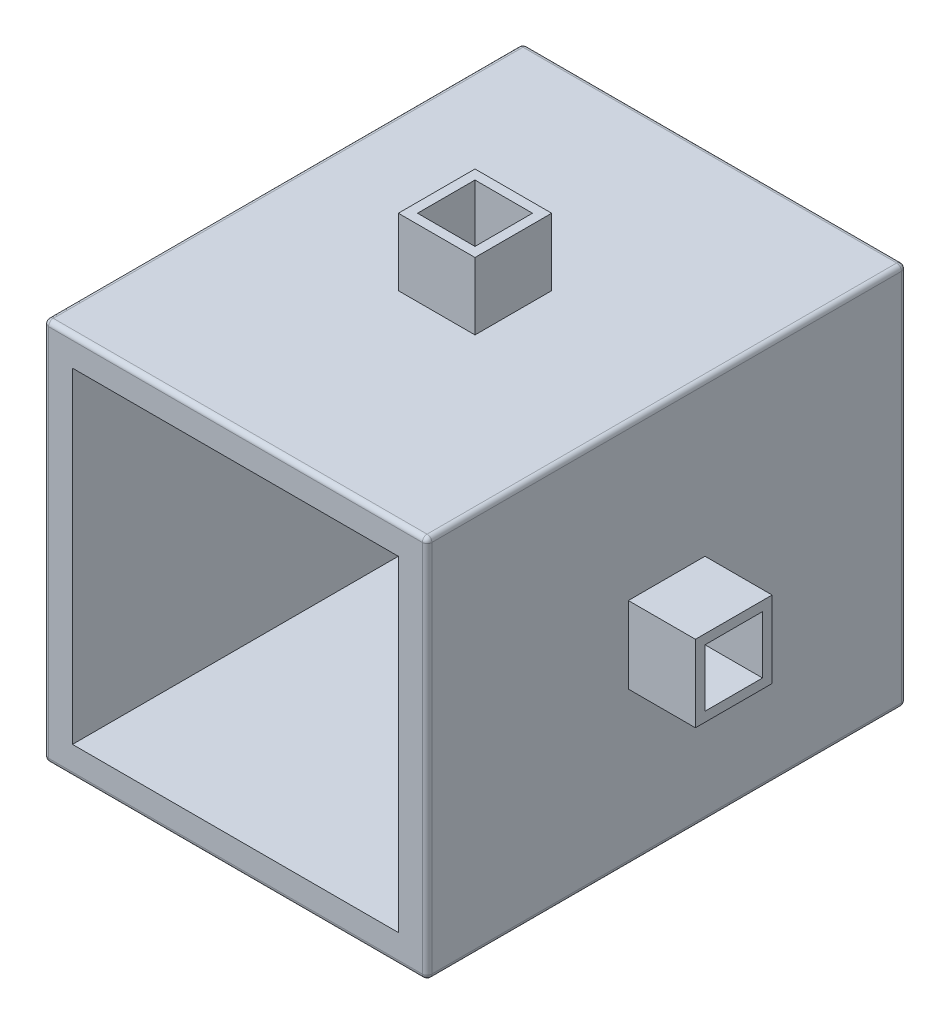
SolidWorks part; units mm, degrees
ref_plane "Front Plane" through (0, 0, 0) normal (0, 0, 1) x (1, 0, 0)
ref_plane "Top Plane" through (0, 0, 0) normal (0, 1, 0) x (1, 0, 0)
ref_plane "Right Plane" through (0, 0, 0) normal (1, 0, 0) x (0, 0, -1)
sketch "Sketch1" plane through (0, 0, 0) normal (0, 0, 1) x (1, 0, 0)
  line L1 (50.8, -50.8) -> (-50.8, -50.8)
  line L2 (50.8, -50.8) -> (50.8, 50.8)
  line L3 (50.8, 50.8) -> (-50.8, 50.8)
  line L4 (-50.8, -50.8) -> (-50.8, 50.8)
  line L5 (50.8, -50.8) -> (-50.8, 50.8) construction
  line L6 (50.8, 50.8) -> (-50.8, -50.8) construction
  point P0 (0, 0)
  dimension "D1" = 101.6
  dimension "D2" = 101.6
extrude "Boss-Extrude1" add sketch "Sketch1" along normal blind 127
sketch "Sketch2" plane through (0, 0, 127) normal (0, 0, 1) x (1, 0, 0)
  line L8 (-43.18, 43.18) -> (-43.18, -43.18)
  line L9 (-43.18, -43.18) -> (43.18, -43.18)
  line L10 (43.18, -43.18) -> (43.18, 43.18)
  line L11 (43.18, 43.18) -> (-43.18, 43.18)
  line L12 (-43.18, 43.18) -> (-43.18, -43.18)
  line L13 (-43.18, -43.18) -> (43.18, -43.18)
  line L14 (43.18, -43.18) -> (43.18, 43.18)
  line L15 (43.18, 43.18) -> (-43.18, 43.18)
  dimension "D1" = 7.62
extrude "Cut-Extrude1" cut sketch "Sketch2" against normal blind 116.84
sketch "Sketch4" plane through (0, 50.8, 0) normal (0, 1, 0) x (1, 0, 0)
  line L0 (0, 0) -> (0, -127) construction
  line L1 (10.16, -73.66) -> (-10.16, -73.66)
  line L2 (10.16, -73.66) -> (10.16, -53.34)
  line L3 (10.16, -53.34) -> (-10.16, -53.34)
  line L4 (-10.16, -73.66) -> (-10.16, -53.34)
  line L5 (10.16, -73.66) -> (-10.16, -53.34) construction
  line L6 (10.16, -53.34) -> (-10.16, -73.66) construction
  line L7 (50.8, -127) -> (-50.8, -127) construction
  line L8 (50.8, -63.5) -> (-50.8, -63.5) construction
  line L9 (50.8, -127) -> (50.8, 0) construction
  line L10 (-50.8, -127) -> (-50.8, 0) construction
  line L11 (7.62, -55.88) -> (-7.62, -55.88)
  line L12 (-7.62, -71.12) -> (-7.62, -55.88)
  line L13 (7.62, -71.12) -> (-7.62, -71.12)
  line L14 (7.62, -71.12) -> (7.62, -55.88)
  point P0 (0, -63.5)
  dimension "D1" = 20.32
  dimension "D2" = 20.32
  dimension "D3" = 2.54
extrude "Boss-Extrude2" add sketch "Sketch4" along normal blind 17.78
sketch "Sketch6" plane through (0, 50.8, 0) normal (0, 1, 0) x (1, 0, 0)
  line L0 (0, 0) -> (0, -127) construction
  line L1 (50.8, -127) -> (-50.8, -127) construction
  line L2 (50.8, -63.5) -> (-50.8, -63.5) construction
  line L3 (50.8, -127) -> (50.8, 0) construction
  line L4 (-50.8, -127) -> (-50.8, 0) construction
  circle A0 centre (0, -63.5) radius 7.62
  dimension "D1" = 15.24
extrude "Cut-Extrude2" cut sketch "Sketch6" against normal blind 1.27
mirror "Mirror1" about plane through (0, 0, 0) normal (0, 1, 0) of "Cut-Extrude2", "Boss-Extrude2"
sketch "Sketch7" plane through (50.8, 0, 0) normal (1, 0, 0) x (0, 0, -1)
  line L0 (-63.5, 50.8) -> (-63.5, -50.8) construction
  line L1 (-127, 50.8) -> (0, 50.8) construction
  line L2 (-127, -50.8) -> (0, -50.8) construction
  line L3 (0, 0) -> (-127, 0) construction
  line L4 (-127, -50.8) -> (-127, 50.8) construction
  line L6 (-53.34, -10.16) -> (-73.66, -10.16)
  line L7 (-53.34, -10.16) -> (-53.34, 10.16)
  line L8 (-53.34, 10.16) -> (-73.66, 10.16)
  line L9 (-73.66, -10.16) -> (-73.66, 10.16)
  line L10 (-53.34, -10.16) -> (-73.66, 10.16) construction
  line L11 (-53.34, 10.16) -> (-73.66, -10.16) construction
  line L12 (-55.88, -7.62) -> (-71.12, -7.62)
  line L13 (-71.12, -7.62) -> (-71.12, 7.62)
  line L14 (-55.88, 7.62) -> (-71.12, 7.62)
  line L15 (-55.88, -7.62) -> (-55.88, 7.62)
  point P11 (-63.5, 0)
  dimension "D1" = 20.32
  dimension "D2" = 20.32
  dimension "D3" = 2.54
extrude "Boss-Extrude3" add sketch "Sketch7" along normal blind 17.78
sketch "Sketch9" plane through (50.8, 0, 0) normal (1, 0, 0) x (0, 0, -1)
  circle A0 centre (-63.5, 0) radius 7.62
  dimension "D1" = 15.24
extrude "Cut-Extrude3" cut sketch "Sketch9" against normal blind 1.27
mirror "Mirror2" about plane through (0, 0, 0) normal (1, 0, 0) of "Cut-Extrude3", "Boss-Extrude3"
fillet "Fillet1" radius 1.27 12 edges at (-50.8, 0, 0) (0, 50.8, 0) (-50.8, 50.8, 63.5) (50.8, 50.8, 63.5) (50.8, 0, 0) (0, -50.8, 0) (-50.8, -50.8, 63.5) (50.8, -50.8, 63.5) (-50.8, 0, 127) (0, 50.8, 127) (50.8, 0, 127) (0, -50.8, 127)
